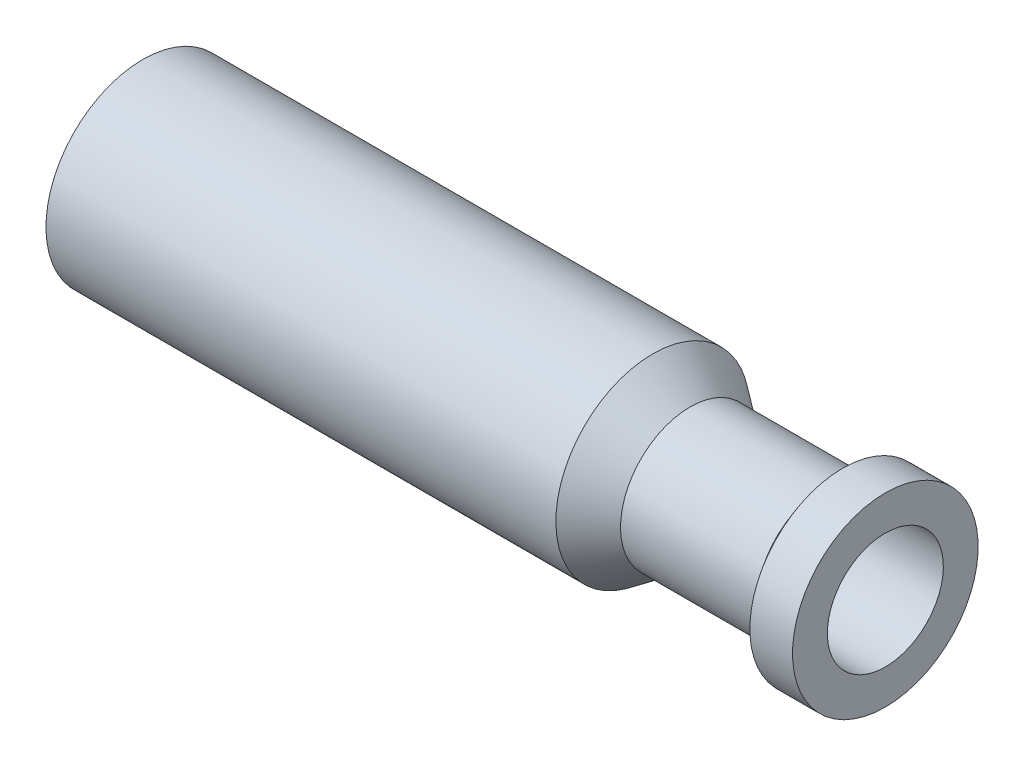
SolidWorks part; units mm, degrees
ref_plane "Front Plane" through (0, 0, 0) normal (0, 0, 1) x (1, 0, 0)
ref_plane "Top Plane" through (0, 0, 0) normal (0, 1, 0) x (1, 0, 0)
ref_plane "Right Plane" through (0, 0, 0) normal (1, 0, 0) x (0, 0, -1)
sketch "Sketch1" plane through (0, 0, 0) normal (0, 0, 1) x (1, 0, 0)
  line L1 (107.503, -15.9109) -> (117.7152, -23.3861)
  line L2 (117.7152, -23.3861) -> (154.8187, -23.3861)
  line L3 (154.8187, -23.3861) -> (159.4668, -17.0361)
  line L4 (159.4668, -17.0361) -> (171.1455, -17.0361)
  line L5 (171.1455, -17.0361) -> (171.1455, -42.4361)
  line L6 (171.1455, -42.4361) -> (-31.8619, -42.4361) construction
  line L8 (-32.0545, -42.4361) -> (171.1455, -42.4361)
  line L9 (107.503, -15.9109) -> (-32.0545, -15.9109)
  line L10 (-32.0545, -15.9109) -> (-32.0545, -42.4361)
  dimension "D1" = 25.4
  dimension "D3" = 19.05
  dimension "D4" = 203.2
revolve "Revolve1" add sketch "Sketch1" angle 360 about L6
sketch "Sketch4" plane through (171.1455, 0, 0) normal (1, 0, 0) x (0, 0, -1)
  circle A0 centre (0, -42.4361) radius 15.875
  dimension "D1" = 31.75
extrude "Cut-Extrude1" cut sketch "Sketch4" against normal blind 190.5
